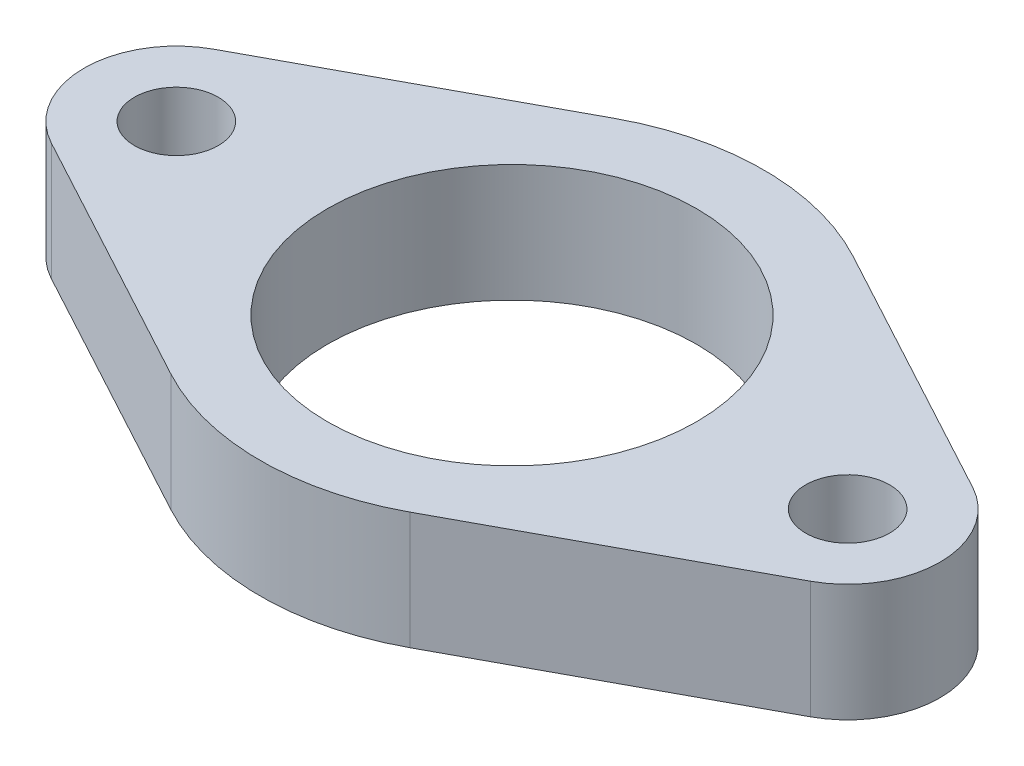
SolidWorks part; units mm, degrees
ref_plane "Front Plane" through (0, 0, 0) normal (0, 0, 1) x (1, 0, 0)
ref_plane "Top Plane" through (0, 0, 0) normal (0, 1, 0) x (1, 0, 0)
ref_plane "Right Plane" through (0, 0, 0) normal (1, 0, 0) x (0, 0, -1)
sketch "Sketch1" plane through (0, 0, 0) normal (0, 1, 0) x (1, 0, 0)
  line L1 (0, 0) -> (-20, 0) construction
  line L2 (-22.6125, 4.8399) -> (-7.125, 13.1998)
  line L3 (-22.6125, -4.8399) -> (-7.125, -13.1998)
  line L4 (0, 4.3007) -> (0, -2.8749) construction
  line L5 (22.6125, -4.8399) -> (7.125, -13.1998)
  line L6 (22.6125, 4.8399) -> (7.125, 13.1998)
  circle A0 centre (0, 0) radius 11
  arc A4 (-7.125, -13.1998) -> (7.125, -13.1998) centre (0, 0) ccw
  circle A5 centre (-20, 0) radius 2.5
  arc A7 (-22.6125, 4.8399) -> (-22.6125, -4.8399) centre (-20, 0) ccw
  circle A8 centre (-20, 0) radius 5.5 construction
  circle A9 centre (0, 0) radius 15 construction
  arc A10 (22.6125, 4.8399) -> (22.6125, -4.8399) centre (20, 0) cw
  circle A11 centre (20, 0) radius 2.5
  arc A12 (7.125, 13.1998) -> (-7.125, 13.1998) centre (0, 0) ccw
  dimension "D1" = 22
  dimension "D2" = 4
  dimension "D5" = 5
  dimension "D7" = 3
  dimension "D6" = 20
extrude "Boss-Extrude1" add sketch "Sketch1" along normal blind 7
